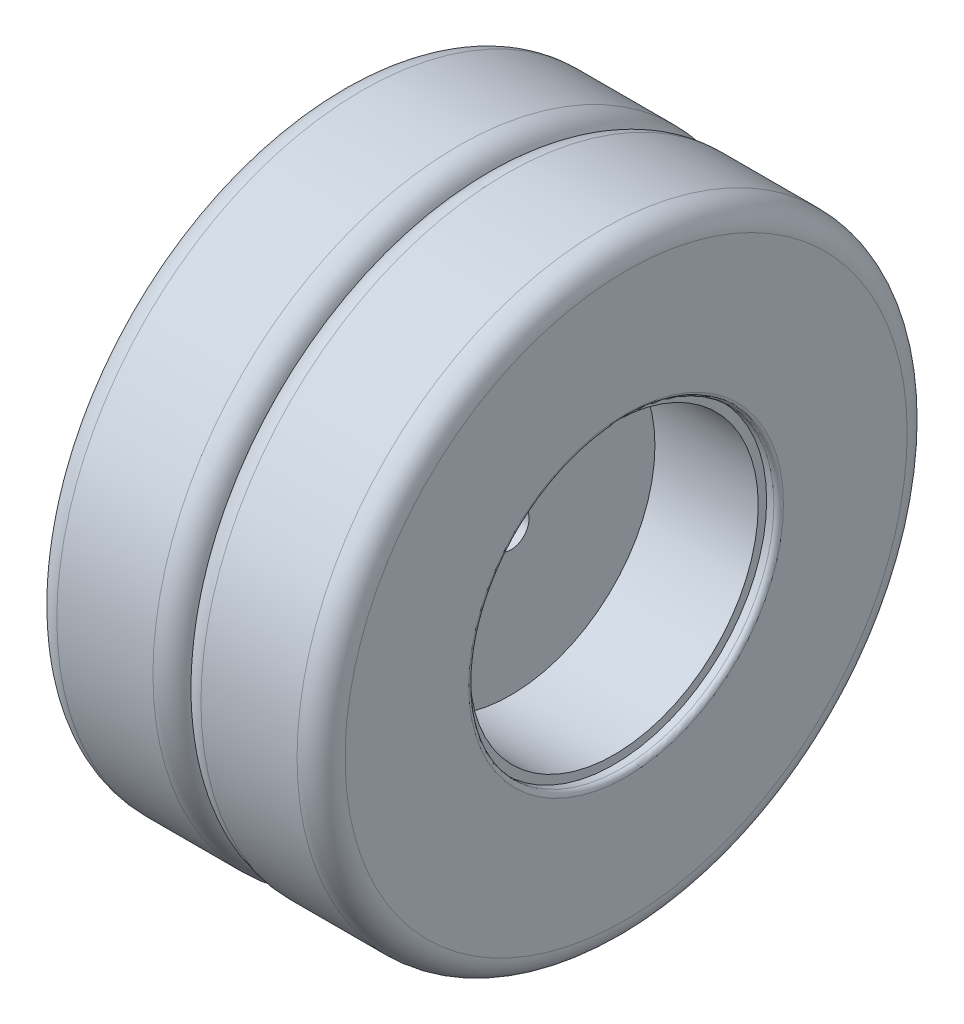
SolidWorks part; units mm, degrees
other "LHS Wheel"
other "RHS Wheel" parameters "D1"=13.6453, "D2"=113.5139, "D3"=155.7266, "D4"=155.7266
ref_plane "Front Plane" through (0, 0, 0) normal (0, 0, 1) x (1, 0, 0)
ref_plane "Top Plane" through (0, 0, 0) normal (0, 1, 0) x (1, 0, 0)
ref_plane "Right Plane" through (0, 0, 0) normal (1, 0, 0) x (0, 0, -1)
sketch "Sketch1" plane through (0, 0, 0) normal (1, 0, 0) x (0, 0, -1)
  circle A1 centre (0, 0) radius 7.625
  circle A2 centre (0, 0) radius 63.5
  dimension "D1" = 15.25
  dimension "D3" = 127
extrude "Hub Face" add sketch "Sketch1" along normal blind 7 from offset 5
sketch "Sketch2" plane through (0, 0, 0) normal (1, 0, 0) x (0, 0, -1)
  circle A0 centre (0, 0) radius 63.5
  circle A1 centre (0, 0) radius 60
  dimension "D1" = 127
  dimension "D2" = 120
extrude "Hub" add sketch "Sketch2" along normal blind 50 from offset 5
sketch "Sketch3" plane through (0, 0, 0) normal (1, 0, 0) x (0, 0, -1)
  circle A0 centre (0, 0) radius 127
  circle A1 centre (0, 0) radius 63.5
  dimension "D1" = 254
  dimension "D2" = 127
extrude "Rubber" add sketch "Sketch3" along normal blind 60
fillet "Fillet1" radius 10 2 edges at (0, 0, -127) (60, 0, -127)
fillet "Fillet2" radius 2 2 edges at (60, 0, -63.5) (0, 0, -63.5)
mirror "Mirror1" about plane through (0, 0, 0) normal (1, 0, 0) of bodies 103
equation "\"tireWidth\"= 60mm"
equation "\"tireDiameter\"= 10in"
equation "\"shaftDiameter\"= 15mm"
equation "\"hubDiameter\"= 5in"
equation "\"D1@Sketch1\"=\"shaftDiameter\" + 0.25mm"
equation "\"hubMaterialThickness\"= 7mm"
equation "\"D1@Hub Face\" = \"hubMaterialThickness\""
equation "\"D3@Sketch1\"=\"hubDiameter\""
equation "\"D1@Sketch2\"=\"hubDiameter\""
equation "\"D2@Sketch2\"=\"hubDiameter\"-\"hubMaterialThickness\""
equation "\"D1@Hub\"=\"hubWidth\""
equation "\"D1@Sketch3\"=\"tireDiameter\""
equation "\"D2@Sketch3\"=\"hubDiameter\""
equation "\"D1@Rubber\" = \"tireWidth\""
equation "\"hubWidth\"= 50mm"
equation "\"D19@Hub\"=(\"tireWidth\"-\"hubWidth\")/2"
equation "\"D19@Hub Face\"=(\"tireWidth\"-\"hubWidth\")/2"
